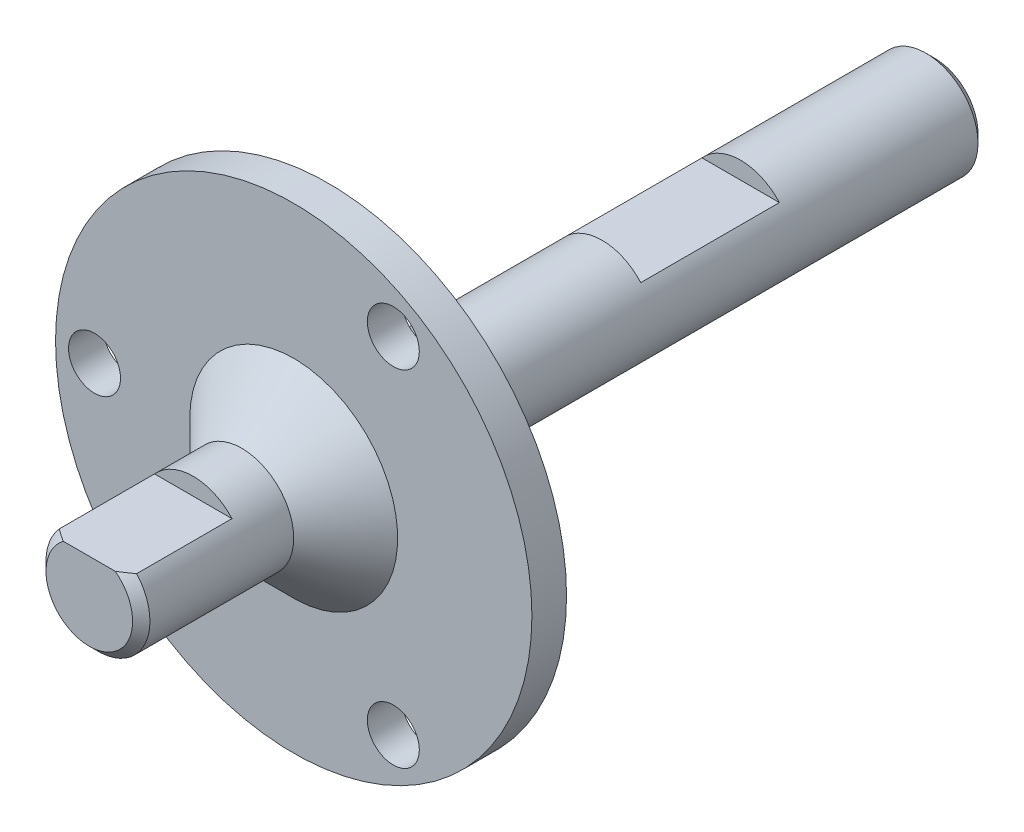
SolidWorks part; units mm, degrees
material "AISI 304"
ref_plane "前视基准面" through (0, 0, 0) normal (0, 0, 1) x (1, 0, 0)
ref_plane "上视基准面" through (0, 0, 0) normal (0, 1, 0) x (1, 0, 0)
ref_plane "右视基准面" through (0, 0, 0) normal (1, 0, 0) x (0, 0, -1)
sketch "草图1" plane through (0, 0, 0) normal (1, 0, 0) x (0, 0, -1)
  line L0 (-33.541, 0) -> (28.918, 0) construction
  line L1 (0, 0) -> (0, 3)
  line L2 (0, 3) -> (11.8, 3)
  line L3 (11.8, 3) -> (11.8, 13.75)
  line L4 (11.8, 13.75) -> (13.8, 13.75)
  line L5 (13.8, 13.75) -> (13.8, 3)
  line L6 (13.8, 3) -> (48.8, 3)
  line L7 (48.8, 3) -> (48.8, 0)
  line L8 (0, 0) -> (48.8, 0)
  dimension "D1" = 2
  dimension "D2" = 6
  dimension "D3" = 27.5
  dimension "D4" = 35
  dimension "D5" = 11.8
revolve "旋转1" add sketch "草图1" angle 360 about L0
sketch "草图2" plane through (0, 0, 0) normal (0, 1, 0) x (1, 0, 0)
  line L1 (-3, 37.6) -> (3, 37.6)
  line L2 (-3, 37.6) -> (-3, 29.6)
  line L3 (-3, 29.6) -> (3, 29.6)
  line L4 (3, 37.6) -> (3, 29.6)
  line L5 (-3, 37.6) -> (3, 29.6) construction
  line L6 (-3, 29.6) -> (3, 37.6) construction
  line L11 (-3, 0) -> (3, 0) construction
  line L12 (-3, 6) -> (3, 6)
  line L14 (-3, 6) -> (-3, 0)
  line L15 (-3, 0) -> (3, 0)
  line L16 (3, 6) -> (3, 0)
  line L17 (-3, 6) -> (3, 0) construction
  line L18 (-3, 0) -> (3, 6) construction
  line L19 (0, 3) -> (0, 0) construction
  point P0 (0, 33.6)
  point P5 (0, 3)
  point P13 (6.5076, 37.6)
  dimension "D1" = 8
  dimension "D2" = 6
  dimension "D3" = 6
  dimension "D4" = 6
  dimension "D5" = 33.6
extrude "切除-拉伸1" cut sketch "草图2" against normal blind 1 from offset 3
chamfer "倒角1" distance 3 angle 45 1 edges at (3, 0, -11.8)
sketch "草图3" plane through (0, 0, -11.8) normal (0, 0, 1) x (1, 0, 0)
  circle A0 centre (0, 0) radius 11.5 construction
  circle A1 centre (5.75, -9.9593) radius 1.5
  circle A2 centre (-11.5, 0) radius 1.5
  circle A3 centre (5.75, 9.9593) radius 1.5
  point P5 (-19.8257, 6.4204)
  point P6 (0, 0)
  point P11 (0, 0)
  point P12 (-9.9593, 5.7499)
  point P13 (-11.5, 0)
  point P14 (-11.5, 0)
  point P15 (-11.5, 0)
  dimension "D1" = 23
  dimension "D2" = 3
  dimension "D3" = 3
extrude "切除-拉伸4" cut sketch "草图3" against normal through all
chamfer "倒角2" distance 0.5 angle 45 2 edges at (0, -3, 0) (3, 0, -48.8)
